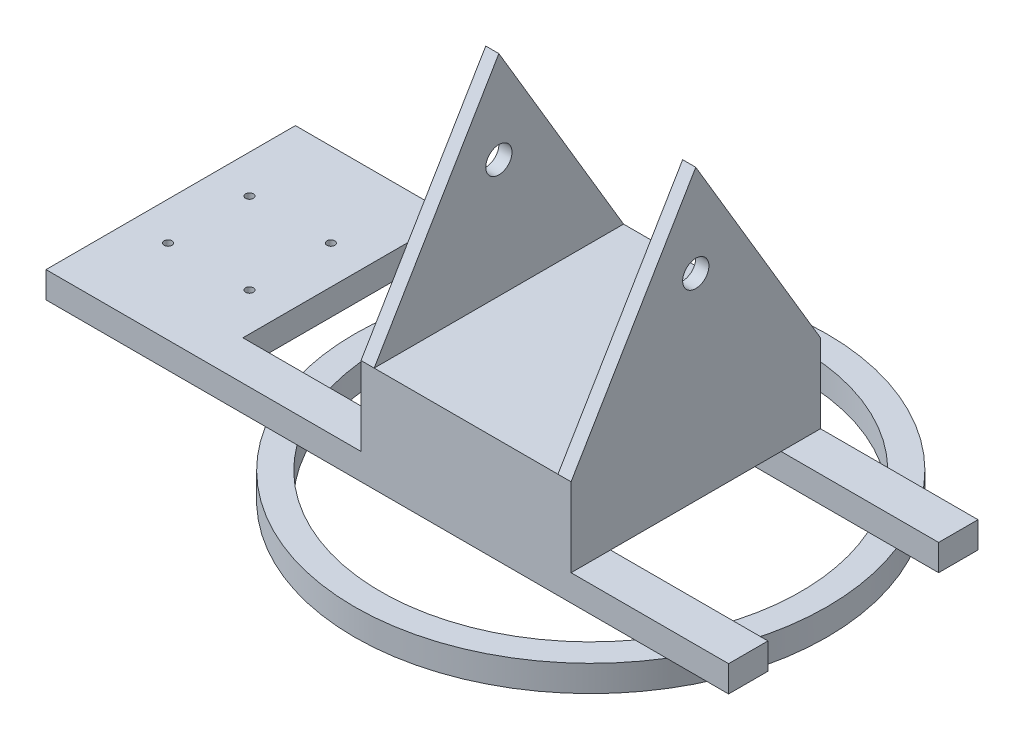
SolidWorks part; units mm, degrees
ref_plane "Front Plane" through (0, 0, 0) normal (0, 0, 1) x (1, 0, 0)
ref_plane "Top Plane" through (0, 0, 0) normal (0, 1, 0) x (1, 0, 0)
ref_plane "Right Plane" through (0, 0, 0) normal (1, 0, 0) x (0, 0, -1)
sketch "Sketch1" plane through (0, 0, 0) normal (0, 1, 0) x (1, 0, 0)
  circle A0 centre (0, 0) radius 90
  circle A1 centre (0, 0) radius 80
  dimension "D1" = 180
  dimension "D2" = 10
extrude "Boss-Extrude1" add sketch "Sketch1" along normal blind 10
sketch "Sketch2" plane through (0, 0, 0) normal (0, 0, 1) x (1, 0, 0)
  line L0 (0, 0) -> (-90, 0) construction
  line L1 (-90, 0) -> (90, 0) construction
  line L2 (0, 0) -> (0, 55.0975) construction
  circle A0 centre (-85, 0) radius 2.5
  dimension "D1" = 5
  dimension "D2" = 5
  dimension "D3" = 90
revolve "Cut-Revolve1" cut sketch "Sketch2" angle 360 about L2
sketch "Sketch3" plane through (0, 10, 0) normal (0, 1, 0) x (1, 0, 0)
  line L0 (-107.8637, 0) -> (120.1803, 0) construction
  line L1 (-100, -32.5) -> (100, -32.5)
  line L2 (-100, 47.5) -> (100, 47.5)
  line L3 (-100, 47.5) -> (-100, 32.5)
  line L4 (-100, 32.5) -> (100, 32.5)
  line L5 (100, 47.5) -> (100, 32.5)
  line L6 (-100, 47.5) -> (100, 32.5) construction
  line L7 (-100, 32.5) -> (100, 47.5) construction
  line L8 (100, -47.5) -> (100, -32.5)
  line L9 (-100, -47.5) -> (100, -47.5)
  line L10 (-100, -47.5) -> (-100, -32.5)
  point P3 (0, 40)
  dimension "D1" = 200
  dimension "D2" = 40
  dimension "D3" = 15
extrude "Boss-Extrude2" add sketch "Sketch3" along normal blind 10
sketch "Sketch5" plane through (0, 10, 0) normal (0, -1, 0) x (1, 0, 0)
  line L0 (-100, 47.5) -> (-76.4444, 47.5) construction
  line L1 (-100, -47.5) -> (-160, -47.5)
  line L2 (-100, -47.5) -> (-100, 47.5)
  line L3 (-100, 47.5) -> (-160, 47.5)
  line L4 (-160, -47.5) -> (-160, 47.5)
  line L5 (-130, -69.1417) -> (-130, 74.349) construction
  line L6 (-176.3836, 0) -> (-91.62, 0) construction
  circle A0 centre (-145.5, -15.5) radius 1.5
  circle A1 centre (-114.5, -15.5) radius 1.5
  circle A2 centre (-114.5, 15.5) radius 1.5
  circle A3 centre (-145.5, 15.5) radius 1.5
  point P7 (-130, 47.5)
  point P8 (-130, -47.5)
  point P11 (-160, 0)
  point P12 (-100, 0)
  dimension "D4" = 3
  dimension "D1" = 60
  dimension "D2" = 31
  dimension "D3" = 31
extrude "Boss-Extrude3" add sketch "Sketch5" against normal blind 10
sketch "Sketch7" plane through (0, 10, 0) normal (0, -1, 0) x (1, 0, 0)
  line L0 (0, 0) -> (-130, 0) construction
  line L1 (-151.15, 21.15) -> (-108.85, 21.15)
  line L2 (-151.15, 21.15) -> (-151.15, -21.15)
  line L3 (-151.15, -21.15) -> (-108.85, -21.15)
  line L4 (-108.85, 21.15) -> (-108.85, -21.15)
  line L5 (-151.15, 21.15) -> (-108.85, -21.15) construction
  line L6 (-151.15, -21.15) -> (-108.85, 21.15) construction
  line L7 (-152.15, 22.15) -> (-152.15, -22.15)
  line L8 (-152.15, -22.15) -> (-107.85, -22.15)
  line L9 (-107.85, 22.15) -> (-107.85, -22.15)
  line L10 (-152.15, 22.15) -> (-107.85, 22.15)
  circle A0 centre (-145.5, 15.5) radius 1.5 construction
  circle A1 centre (-145.5, -15.5) radius 1.5 construction
  circle A2 centre (-114.5, -15.5) radius 1.5 construction
  circle A3 centre (-114.5, 15.5) radius 1.5 construction
  circle A4 centre (-145.5, -15.5) radius 1.5
  circle A5 centre (-114.5, -15.5) radius 1.5
  circle A6 centre (-114.5, 15.5) radius 1.5
  circle A7 centre (-145.5, 15.5) radius 1.5
  point P0 (-130, 0)
  dimension "D1" = 42.3
  dimension "D2" = 42.3
  dimension "D3" = 130
  dimension "D4" = 1
extrude "Boss-Extrude4" add sketch "Sketch7" along normal blind 5 contours L10 L7 L8 L9 L1 L4 L3 L2
sketch "Sketch8" plane through (0, 0, 0) normal (1, 0, 0) x (0, 0, -1)
  line L1 (0, 0) -> (0, 20) construction
  line L2 (-90, 0) -> (90, 0) construction
  line L3 (32.5, 20) -> (-32.5, 20) construction
  line L5 (-47.5, 20) -> (47.5, 20)
  line L6 (-47.5, 20) -> (-47.5, 50)
  line L7 (-47.5, 50) -> (47.5, 50)
  line L8 (47.5, 20) -> (47.5, 50)
  dimension "D1" = 95
  dimension "D2" = 30
extrude "Boss-Extrude5" add sketch "Sketch8" along normal mid plane 70
sketch "Sketch9" plane through (-35, 0, 0) normal (-1, 0, 0) x (0, 0, 1)
  line L0 (-47.5, 50) -> (0, 130)
  line L1 (0, 130) -> (47.5, 50)
  line L2 (0, 0) -> (0, 199.3066) construction
  line L3 (-47.5, 50) -> (47.5, 50) construction
  line L5 (-47.5, 50) -> (-47.5, 20)
  line L6 (-47.5, 20) -> (47.5, 20)
  line L7 (47.5, 20) -> (47.5, 50)
  dimension "D1" = 80
extrude "Boss-Extrude7" add sketch "Sketch9" along normal blind 5
mirror "Mirror1" about plane through (0, 0, 0) normal (1, 0, 0) of "Boss-Extrude7"
sketch "Sketch10" plane through (-40, 0, 0) normal (-1, 0, 0) x (0, 0, 1)
  line L0 (0, 0) -> (0, 95) construction
  circle A0 centre (0, 95) radius 5
  point P3 (0, 140)
  dimension "D1" = 10
  dimension "D2" = 95
extrude "Cut-Extrude1" cut sketch "Sketch10" against normal through all
